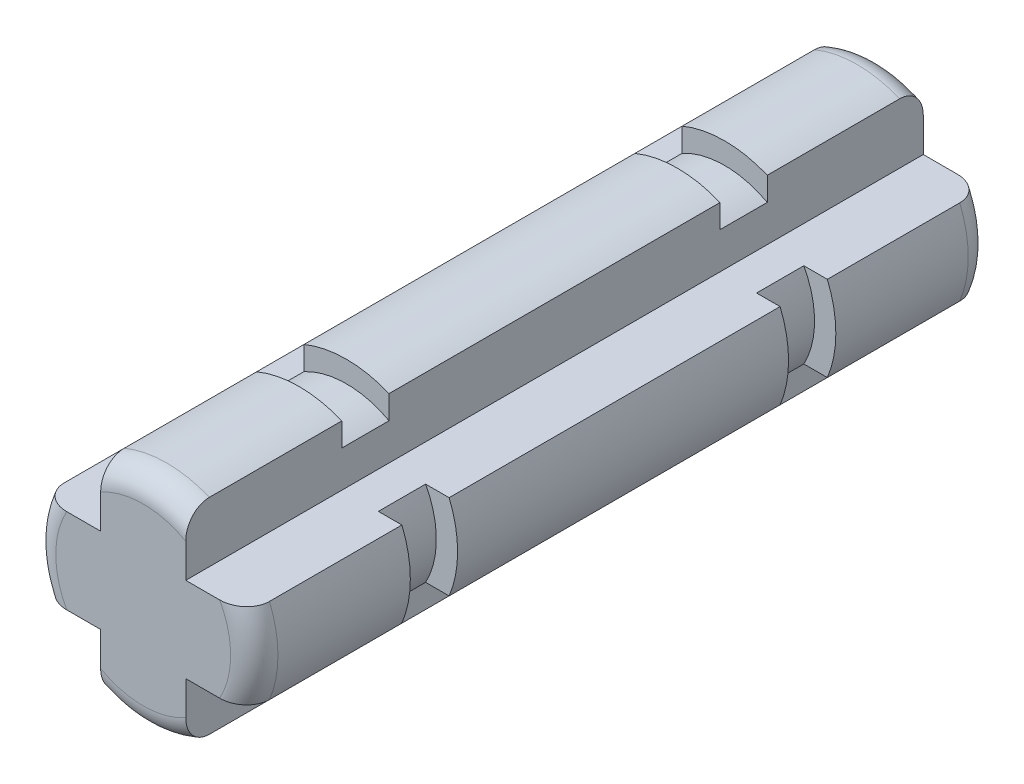
SolidWorks part; units mm, degrees
ref_plane "Front Plane" through (0, 0, 0) normal (0, 0, 1) x (1, 0, 0)
ref_plane "Top Plane" through (0, 0, 0) normal (0, 1, 0) x (1, 0, 0)
ref_plane "Right Plane" through (0, 0, 0) normal (1, 0, 0) x (0, 0, -1)
sketch "Sketch1" plane through (0, 0, 0) normal (0, 0, 1) x (1, 0, 0)
  line L1 (0.9, -2.35) -> (-0.9, -2.35)
  line L2 (0.9, -2.35) -> (0.9, 2.35)
  line L3 (0.9, 2.35) -> (-0.9, 2.35)
  line L4 (-0.9, -2.35) -> (-0.9, 2.35)
  line L5 (0.9, -2.35) -> (-0.9, 2.35) construction
  line L6 (0.9, 2.35) -> (-0.9, -2.35) construction
  line L7 (2.35, -0.9) -> (-2.35, -0.9)
  line L8 (2.35, -0.9) -> (2.35, 0.9)
  line L9 (2.35, 0.9) -> (-2.35, 0.9)
  line L10 (-2.35, -0.9) -> (-2.35, 0.9)
  line L11 (2.35, -0.9) -> (-2.35, 0.9) construction
  line L12 (2.35, 0.9) -> (-2.35, -0.9) construction
  circle A0 centre (0, 0) radius 2.35
  point P0 (0, 0)
  point P6 (0, 0)
  dimension "D1" = 1.8
  dimension "D2" = 4.7
extrude "Boss-Extrude1" add sketch "Sketch1" along normal mid plane 15.6 contours L2 A0 L4 L9 | A0 L9 L2 L7 | L4 A0 L2 L7 | L9 A0 L7 L4 | L2 L9 L4 L7
fillet "Fillet1" radius 0.5 8 edges at (-2.35, 0, 7.8) (2.35, 0, 7.8) (2.35, 0, -7.8) (-2.35, 0, -7.8) (0, 2.35, 7.8) (0, -2.35, 7.8) (0, -2.35, -7.8) (0, 2.35, -7.8)
sketch "Sketch2" plane through (0, 0, 0) normal (0, 0, 1) x (1, 0, 0)
  circle A0 centre (0, 0) radius 1.9
  dimension "D1" = 3.8
extrude "Side Cut" cut sketch "Sketch2" along normal blind 1 from offset 3.5 flip side to cut
mirror "Mirror1" about plane through (0, 0, 0) normal (0, 0, 1) of "Side Cut"
